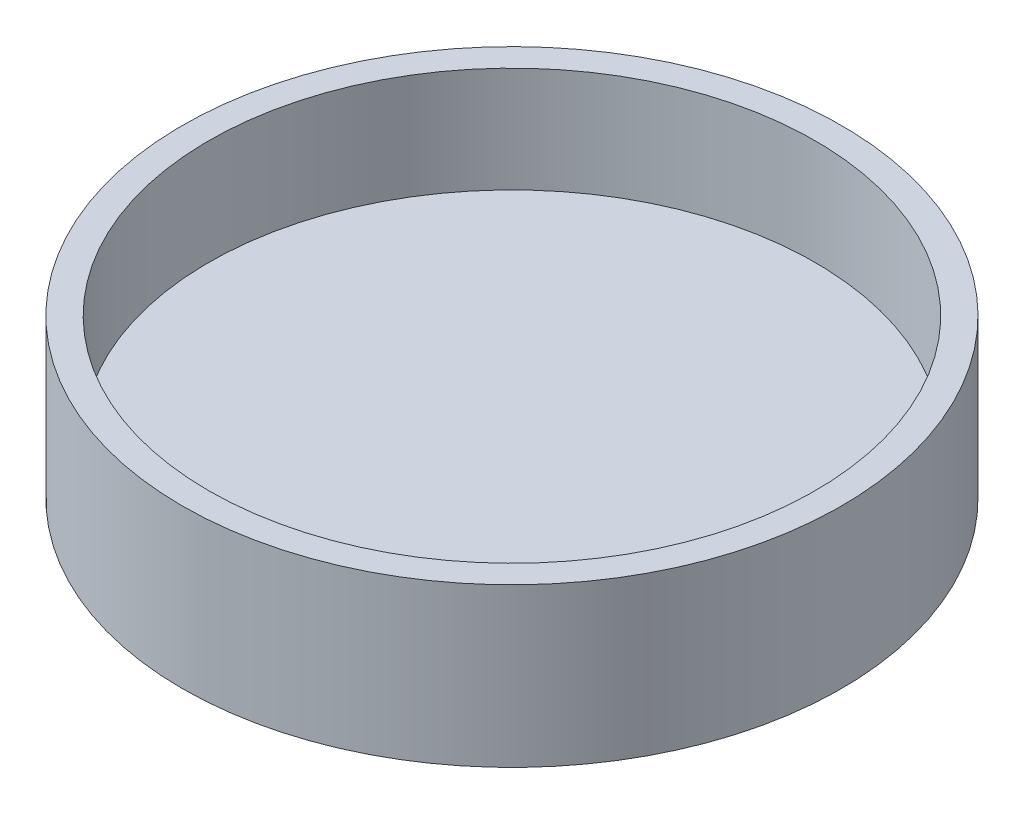
SolidWorks part; units mm, degrees
ref_plane "Front Plane" through (0, 0, 0) normal (0, 0, 1) x (1, 0, 0)
ref_plane "Top Plane" through (0, 0, 0) normal (0, 1, 0) x (1, 0, 0)
ref_plane "Right Plane" through (0, 0, 0) normal (1, 0, 0) x (0, 0, -1)
sketch "Sketch1" plane through (0, 0, 0) normal (0, 1, 0) x (1, 0, 0)
  circle A0 centre (0, 0) radius 158.75
  dimension "D1" = 317.5
extrude "Boss-Extrude1" add sketch "Sketch1" along normal blind 25.4
sketch "Sketch2" plane through (0, 25.4, 0) normal (0, 1, 0) x (1, 0, 0)
  circle A0 centre (0, 0) radius 146.05
  circle A1 centre (0, 0) radius 158.75
  circle A2 centre (0, 0) radius 158.75
  dimension "D2" = 292.1
  dimension "D1" = 0
extrude "Boss-Extrude2" add sketch "Sketch2" along normal blind 50.8
